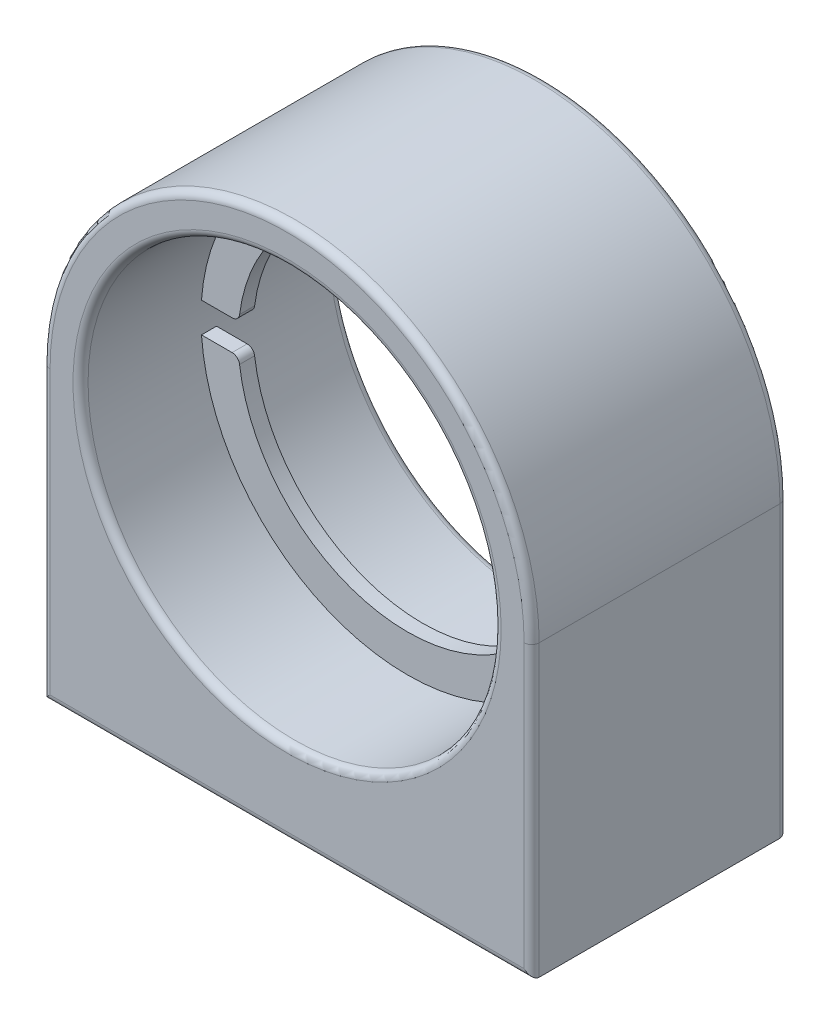
SolidWorks part; units mm, degrees
ref_plane "Ebene vorne" through (0, 0, 0) normal (0, 0, 1) x (1, 0, 0)
ref_plane "Ebene oben" through (0, 0, 0) normal (0, 1, 0) x (1, 0, 0)
ref_plane "Ebene rechts" through (0, 0, 0) normal (1, 0, 0) x (0, 0, -1)
sketch "Skizze1" plane through (0, 0, 0) normal (0, 0, 1) x (1, 0, 0)
  line L0 (0, 51.75) -> (-6.6729, 51.75) construction
  line L1 (-32.5, -19.25) -> (32.5, -19.25)
  line L2 (-32.5, -19.25) -> (-32.5, 19.25)
  line L3 (-32.5, 19.25) -> (32.5, 19.25)
  line L4 (32.5, -19.25) -> (32.5, 19.25)
  line L5 (-32.5, -19.25) -> (32.5, 19.25) construction
  line L6 (-32.5, 19.25) -> (32.5, -19.25) construction
  circle A0 centre (0, 19.25) radius 32.5
  circle A1 centre (0, 19.25) radius 22.5
  point P0 (0, 0)
  dimension "D3" = 45
  dimension "D1" = 71
  dimension "D2" = 65
extrude "Aufsatz-Linear austragen1" add sketch "Skizze1" along normal mid plane 34 contours A1 L3 A0 | A1 L3 A0 | A0 L2 L1 L4
sketch "Skizze3" plane through (0, 0, 17) normal (0, 0, 1) x (1, 0, 0)
  circle A0 centre (0, 19.25) radius 27.45
  dimension "D1" = 54.9
extrude "Schnitt-Linear austragen1" cut sketch "Skizze3" against normal blind 16
mirror "Spiegeln1" about plane through (0, 0, 0) normal (0, 0, 1) of "Schnitt-Linear austragen1"
sketch "Skizze4" plane through (0, -19.25, 0) normal (0, -1, 0) x (1, 0, 0)
  line L0 (-32.5, 0) -> (32.5, 0) construction
  line L1 (-32.5, 17) -> (-32.5, -17) construction
  line L2 (32.5, 17) -> (32.5, -17) construction
  line L3 (-32.5, 0) -> (-22.5, 0) construction
  line L4 (0, 0) -> (0, 6.6092) construction
  circle A0 centre (-22.5, 0) radius 2.8
  circle A1 centre (-10, 0) radius 2.8
  circle A2 centre (10, 0) radius 2.8
  circle A3 centre (22.5, 0) radius 2.8
  dimension "D3" = 5.6
  dimension "D4" = 5.6
  dimension "D1" = 10
  dimension "D2" = 12.5
extrude "Schnitt-Linear austragen2" cut sketch "Skizze4" against normal blind 11
sketch "Skizze5" plane through (0, 0, 1) normal (0, 0, 1) x (1, 0, 0)
  line L0 (0, 19.25) -> (27.45, 19.25) construction
  line L2 (-27.377, 17.25) -> (27.377, 17.25)
  line L4 (-27.377, 21.25) -> (27.377, 21.25)
  circle A0 centre (0, 19.25) radius 27.45 construction
  circle A1 centre (0, 19.25) radius 27.45
  point P11 (-0.2827, 19.4908)
  circle M5 centre (0, 19.25) radius 22.5
  circle M6 centre (0, 19.25) radius 27.45
  dimension "D1" = 2
  dimension "D2" = 2
extrude "Schnitt-Linear austragen3" cut sketch "Skizze5" against normal up to surface (2 mm away) contours L4 L2 M6 M5 | L0 A1 L4 M5 | L0 L2 M5 M6 up to face at (-22.5, 19.25, -1)
fillet "Verrundung1" radius 1 18 edges at (-32.5, 0, -17) (-32.5, 0, 17) (0, -19.25, -17) (0, -19.25, 17) (32.5, 0, -17) (32.5, 0, 17) (0, 51.75, -17) (0, 51.75, 17) (27.45, 19.25, 17) (27.45, 19.25, -17) (22.5, -19.25, 2.8) (10, -19.25, 2.8) (-10, -19.25, -2.8) (-22.5, -19.25, -2.8) (-22.4109, 17.25, 0) (22.4109, 17.25, 0) (-22.4109, 21.25, 0) (22.4109, 21.25, 0)
